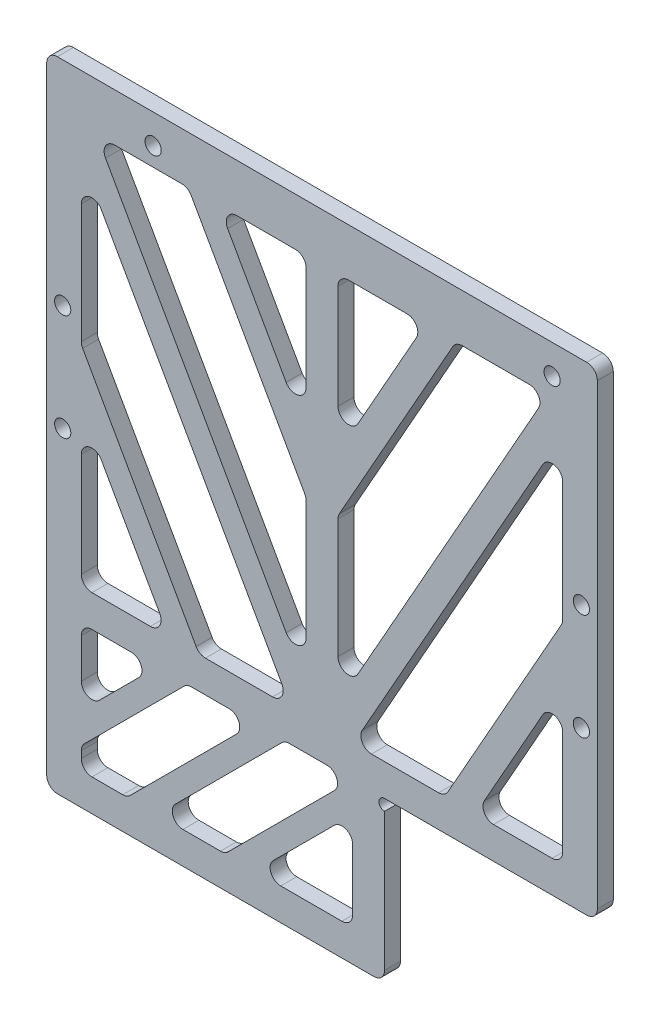
SolidWorks part; units mm, degrees
material "Thornel Mat VMA"
ref_plane "前视基准面" through (0, 0, 0) normal (0, 0, 1) x (1, 0, 0)
ref_plane "上视基准面" through (0, 0, 0) normal (0, 1, 0) x (1, 0, 0)
ref_plane "右视基准面" through (0, 0, 0) normal (1, 0, 0) x (0, 0, -1)
sketch "草图1" plane through (0, 0, 0) normal (0, 0, 1) x (1, 0, 0)
  line L1 (-51.75, -45) -> (51.75, -45)
  line L2 (-51.75, -45) -> (-51.75, 45)
  line L3 (-51.75, 45) -> (51.75, 45)
  line L4 (51.75, -45) -> (51.75, 45)
  line L5 (0, 45) -> (0, -45) construction
  line L6 (-51.75, 0) -> (51.75, 0) construction
  point P0 (0, 0)
  dimension "D1" = 90
  dimension "D2" = 103.5
extrude "凸台-拉伸1" add sketch "草图1" along normal mid plane 3
sketch "草图2" plane through (0, 0, 1.5) normal (0, 0, 1) x (1, 0, 0)
  line L0 (51.75, -45) -> (51.75, 45) construction
  line L1 (-51.75, -45) -> (11.75, -45)
  line L2 (-51.75, -45) -> (-51.75, -75)
  line L3 (-51.75, -75) -> (11.75, -75)
  line L4 (11.75, -45) -> (11.75, -75)
  dimension "D1" = 40
  dimension "D2" = 30
extrude "凸台-拉伸2" add sketch "草图2" against normal up to surface (3 mm away) up to face at (0, 0, -1.5)
sketch "草图3" plane through (0, 0, -1.5) normal (0, 0, -1) x (-1, 0, 0)
  line L0 (-11.75, -75) -> (-11.75, -45) construction
  circle A0 centre (-11.75, -46.05) radius 1.05
  dimension "D1" = 2.1
extrude "切除-拉伸1" cut sketch "草图3" against normal up to surface (3 mm away) up to face at (3.9167, -25, 1.5)
sketch "草图4" plane through (0, 0, 1.5) normal (0, 0, 1) x (1, 0, 0)
  circle A0 centre (43.25, 39.5) radius 1.25 construction
  circle A1 centre (-31.75, 39.5) radius 1.25 construction
  circle A2 centre (43.25, 39.5) radius 1.25 construction
  circle A3 centre (-31.75, 39.5) radius 1.25 construction
  circle A4 centre (-31.75, 39.5) radius 1.525
  circle A5 centre (43.25, 39.5) radius 1.525
  dimension "D1" = 3.05
extrude "切除-拉伸2" cut sketch "草图4" against normal blind 10
sketch "草图5" plane through (0, 0, -1.5) normal (0, 0, -1) x (-1, 0, 0)
  circle A0 centre (48.75, 5) radius 1.25 construction
  circle A1 centre (48.75, -15) radius 1.25 construction
  circle A2 centre (48.75, 5) radius 1.25 construction
  circle A3 centre (48.75, -15) radius 1.25 construction
  circle A4 centre (48.75, -15) radius 1.525
  circle A5 centre (48.75, 5) radius 1.525
  dimension "D1" = 3.05
extrude "切除-拉伸3" cut sketch "草图5" against normal blind 10
mirror "镜向1" about plane through (0, 0, 0) normal (1, 0, 0) of "切除-拉伸3"
fillet "圆角1" radius 2 5 edges at (51.75, -45, 0) (11.75, -75, 0) (-51.75, -75, 0) (-51.75, 45, 0) (51.75, 45, 0)
sketch "草图6" plane through (0, 0, -1.5) normal (0, 0, -1) x (-1, 0, 0)
  line L0 (-45.25, 36) -> (-45.25, -39)
  line L1 (-45.25, -39) -> (-3, -39)
  line L2 (-3, -39) -> (-3, 36)
  line L3 (-3, 36) -> (-45.25, 36)
  line L4 (-11.75, -45) -> (-49.75, -45) construction
  line L5 (-45.25, 36) -> (-3, -39) construction
  line L6 (-45.25, 30.9064) -> (-5.1782, -40.227)
  line L7 (-45.25, 0.3448) -> (-23.0857, -39)
  line L8 (-3, -39) -> (-50.1517, -65.5621) construction
  line L9 (-42.3806, 36) -> (-3, -33.9064)
  line L10 (-45.25, -9.8423) -> (-28.8245, -39)
  line L11 (-19.4255, 36) -> (-3, 6.8423)
  line L12 (-25.1643, 36) -> (-3, -3.3449)
  line L13 (0, 0) -> (0, 42.4212) construction
  line L14 (3, -39) -> (50.1517, -65.5621) construction
  line L15 (45.25, 36) -> (3, -39) construction
  line L16 (25.1643, 36) -> (3, -3.3449)
  line L17 (19.4255, 36) -> (3, 6.8423)
  line L18 (-60.4971, 27.4108) -> (-18.2471, -47.5892) construction
  line L19 (-47.4282, 34.773) -> (-5.1782, -40.227) construction
  line L20 (-45.25, -40.4039) -> (-44.4591, -41.8078) [skipped]
  line L21 (45.25, -9.8423) -> (28.8245, -39)
  line L22 (42.3806, 36) -> (3, -33.9064)
  line L23 (45.25, 0.3448) -> (23.0857, -39)
  line L24 (45.25, 30.9064) -> (5.1782, -40.227)
  line L25 (3, 36) -> (45.25, 36)
  line L26 (3, -39) -> (3, 36)
  line L27 (45.25, -39) -> (3, -39)
  line L28 (45.25, 36) -> (45.25, -39)
  circle A0 centre (31.75, 39.5) radius 1.525 construction
  circle A1 centre (-48.75, 5) radius 1.525 construction
  dimension "D1" = 3.5
  dimension "D2" = 3.5
  dimension "D3" = 6
  dimension "D4" = 3
  dimension "D8" = 20
  dimension "D5" = 2.5
  dimension "D6" = 15
  dimension "D7" = 2
extrude "切除-拉伸4" cut sketch "草图6" against normal blind 10 contours L10 L0 L1 | L0 L7 L1 L6 | L12 L3 L9 L2 | L3 L11 L2 | L26 L17 L25 | L26 L22 L25 L16 | L28 L24 L27 L23 | L28 L21 L27
sketch "草图7" plane through (0, 0, -1.5) normal (0, 0, -1) x (-1, 0, 0)
  line L0 (45.25, -9.8423) -> (45.25, -39) construction
  line L1 (-5.75, -45) -> (45.25, -45)
  line L2 (-5.75, -45) -> (-5.75, -69)
  line L3 (-5.75, -69) -> (45.25, -69)
  line L4 (45.25, -45) -> (45.25, -69)
  line L5 (-11.75, -45) -> (-49.75, -45) construction
  line L6 (-11.75, -73) -> (-11.75, -47.1) construction
  line L7 (49.75, -75) -> (-9.75, -75) construction
  line L10 (-5.75, -45) -> (18.25, -69)
  line L11 (-5.75, -50.6569) -> (12.5931, -69)
  line L12 (6.9779, -45) -> (30.9779, -69)
  line L13 (12.6348, -45) -> (36.6348, -69)
  line L14 (25.3627, -45) -> (45.25, -64.8873)
  line L15 (31.0196, -45) -> (45.25, -59.2304)
  dimension "D1" = 6
  dimension "D2" = 6
  dimension "D3" = 45
  dimension "D4" = 4
  dimension "D5" = 9
  dimension "D6" = 4
  dimension "D7" = 9
  dimension "D8" = 4
extrude "切除-拉伸5" cut sketch "草图7" against normal blind 10 contours L11 L2 L3 | L12 L1 L10 L3 | L14 L1 L13 L3 L4 | L1 L15 L4
fillet "圆角2" radius 2 43 edges at (-45.25, -64.8873, 0) (-45.25, -69, 0) (-36.6348, -69, 0) (-12.6348, -45, 0) (-25.3627, -45, 0) (-45.25, -45, 0) (-45.25, -59.2304, 0) (-31.0196, -45, 0) (-3, 36, 0) (-19.4255, 36, 0) (-3, 6.8423, 0) (3, 6.8423, 0) (19.4255, 36, 0) (3, 36, 0) (5.8694, -39, 0) (23.0857, -39, 0) (45.25, 0.3448, 0) (45.25, 30.9064, 0) (-45.25, -39, 0) (-28.8245, -39, 0) (-45.25, -9.8423, 0) (-45.25, 0.3448, 0) (-23.0857, -39, 0) (-5.8694, -39, 0) (-45.25, 30.9064, 0) (28.8245, -39, 0) (45.25, -39, 0) (45.25, -9.8423, 0) (-3, -3.3449, 0) (-25.1643, 36, 0) (-42.3806, 36, 0) (-3, -33.9064, 0) (3, -3.3449, 0) (3, -33.9064, 0) (42.3806, 36, 0) (25.1643, 36, 0) (5.75, -50.6569, 0) (-30.9779, -69, 0) (-18.25, -69, 0) (5.75, -45, 0) (-6.9779, -45, 0) (-12.5931, -69, 0) (5.75, -69, 0)
equation "\"D2@草图6\"=\"D1@草图6\""
equation "\"D6@草图7\"=\"D4@草图7\""
